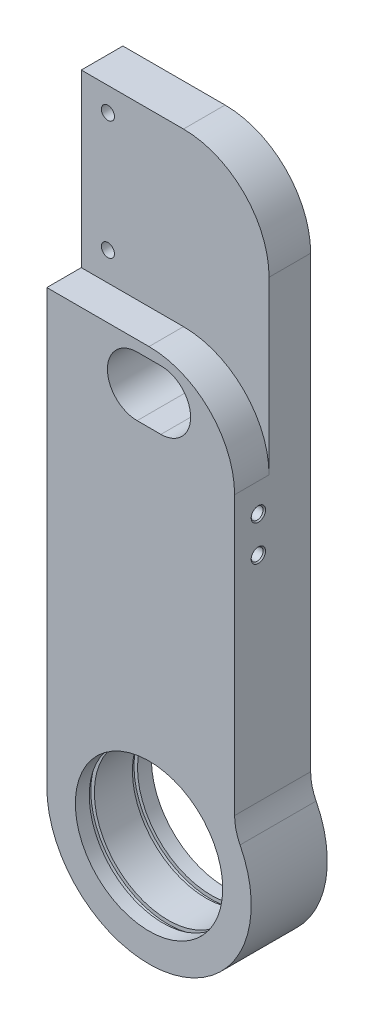
SolidWorks part; units mm, degrees
material "3.3535 (AlMg3) eloxiert"
ref_plane "Vorne" through (0, 0, 0) normal (0, 0, 1) x (1, 0, 0)
ref_plane "Oben" through (0, 0, 0) normal (0, 1, 0) x (1, 0, 0)
ref_plane "Rechts" through (0, 0, 0) normal (1, 0, 0) x (0, 0, -1)
sketch "Skizze1" plane through (0, 0, 0) normal (0, 0, 1) x (1, 0, 0)
  line L0 (36, 29.1033) -> (36, 218)
  line L1 (-43, 0) -> (-43, 254)
  line L2 (-43, 254) -> (0, 254)
  line L3 (5, 165) -> (-5, 165) construction
  line L4 (5, 152.5) -> (-5, 152.5)
  line L5 (5, 177.5) -> (-5, 177.5)
  line L6 (0, 218) -> (0, 0) construction
  arc A0 (38.2969, 19.5538) -> (36, 29.1033) centre (57, 29.1033) cw
  arc A1 (-43, 0) -> (38.2969, 19.5538) centre (0, 0) ccw
  circle A2 centre (0, 0) radius 31
  arc A4 (36, 218) -> (0, 254) centre (0, 218) ccw
  arc A5 (5, 152.5) -> (5, 177.5) centre (5, 165) ccw
  arc A6 (-5, 177.5) -> (-5, 152.5) centre (-5, 165) ccw
  point P12 (0, 165)
  point P19 (-43, 0)
  point P22 (43, 0)
  dimension "D1" = 62
  dimension "D2" = 86
  dimension "D3" = 21
  dimension "D6" = 36
  dimension "D9" = 10
  dimension "D8" = 165
  dimension "D4" = 36
  dimension "D5" = 218
  dimension "D7" = 25
extrude "Aufsatz-Linear austragen1" add sketch "Skizze1" along normal blind 32
sketch "Skizze2" plane through (0, 0, 0) normal (0, 1, 0) x (1, 0, 0)
  line L0 (0, 0) -> (0, -27.414) construction
  line L2 (-32.5, -5.85) -> (-30, -5.85)
  line L3 (-32.5, -5.85) -> (-32.5, -8)
  line L4 (-32.5, -8) -> (-30, -8)
  line L5 (-30, -5.85) -> (-30, -8)
  line L6 (-32.5, -24) -> (-30, -24)
  line L7 (-32.5, -24) -> (-32.5, -26.15)
  line L8 (-32.5, -26.15) -> (-30, -26.15)
  line L9 (-30, -24) -> (-30, -26.15)
  line L10 (-31, -32) -> (31, -32) construction
  dimension "D1" = 16
  dimension "D2" = 30
  dimension "D3" = 65
  dimension "D4" = 2.15
  dimension "D5" = 5.85
revolve "Schnitt-Rotation1" cut sketch "Skizze2" angle 360 about L0
sketch "Skizze3" plane through (0, 0, 32) normal (0, 0, 1) x (1, 0, 0)
  line L0 (-43, 182) -> (0, 182)
  line L1 (36, 29.1033) -> (36, 218) construction
  line L2 (36, 146) -> (92.7966, 146)
  line L3 (92.7966, 146) -> (92.7966, 301.3823)
  line L4 (-43, 182) -> (-43, 301.3823)
  line L5 (-43, 254) -> (-43, 0) construction
  line L6 (92.7966, 301.3823) -> (-43, 301.3823)
  arc A0 (0, 182) -> (36, 146) centre (0, 146) cw
  circle A1 centre (0, 0) radius 31 construction
  dimension "D1" = 182
  dimension "D2" = 36
  dimension "D3" = 56.7966
  dimension "D4" = 155.3823
extrude "Schnitt-Linear austragen1" cut sketch "Skizze3" against normal blind 14.5
hole_wizard "Ø5.5 (5.5) Durchmesser Bohrung1" positions "Skizze5" profile "Skizze4" hole size "Ø5.5" standard "Gabler-Normteile" end condition through all
sketch "Skizze5" plane through (0, 0, 17.5) normal (0, 0, 1) x (1, 0, 0)
  line L1 (-43, 254) -> (-43, 182) construction
  line L2 (0, 254) -> (-43, 254) construction
  point P0 (-31.8, 194)
  point P2 (-31.8, 244)
  dimension "D1" = 11.2
  dimension "D2" = 50
  dimension "D3" = 10
sketch "Skizze4" plane through (-31.8, 194, 17.5) normal (1, 0, 0) x (0, -1, 0)
  line L0 (0, 0) -> (0, 17.5)
  line L1 (0, 17.5) -> (2.75, 17.5)
  line L2 (2.75, 17.5) -> (2.75, 0)
  line L5 (2.75, 0) -> (0, 0)
  line L11 (0, -6.35) -> (0, 107.95) construction
  dimension "Bohrerdurchmesser" = 5.5
  dimension "Bohrungstiefe" = 17.5
hole_wizard "M6 Gewindebohrung1" positions "Skizze7" profile "Skizze6" tap size "M6" standard "Gabler-Normteile"
sketch "Skizze7" plane through (36, 0, -4) normal (-1, 0, 0) x (0, 0, 1)
  line L1 (36, 29.1033) -> (36, 146) construction
  line L3 (21.5, 254) -> (4, 254) construction
  point P2 (26, 134)
  point P15 (26, 119)
  dimension "D1" = 120
  dimension "D2" = 15
  dimension "D3" = 10
sketch "Skizze6" plane through (36, 134, 22) normal (0, 1, 0) x (0, 0, -1)
  line L0 (0, 0) -> (0, 18.5022)
  line L1 (0, 18.5022) -> (2.5, 17)
  line L2 (2.5, 17) -> (2.5, 0.525)
  line L3 (2.5, 0.525) -> (3.025, 0)
  line L5 (3.025, 0) -> (0, 0)
  line L6 (-2.5, 0.525) -> (-3.025, 0) construction
  line L10 (0, 18.5022) -> (-2.5, 17) construction
  line L11 (0, -6.35) -> (0, 107.95) construction
  dimension "Bohrerdurchmesser" = 5
  dimension "Bohrungstiefe" = 17
  dimension "Senkdurchmesser (Oben)" = 6.05
  dimension "Senkwinkel (Oben)" = 90
  dimension "Spitzenwinkel" = 118
cosmetic thread "Bohrungsgewinde1" parameters "D1"=12, "D2"=6
cosmetic thread "Bohrungsgewinde2" parameters "D1"=12, "D2"=6
